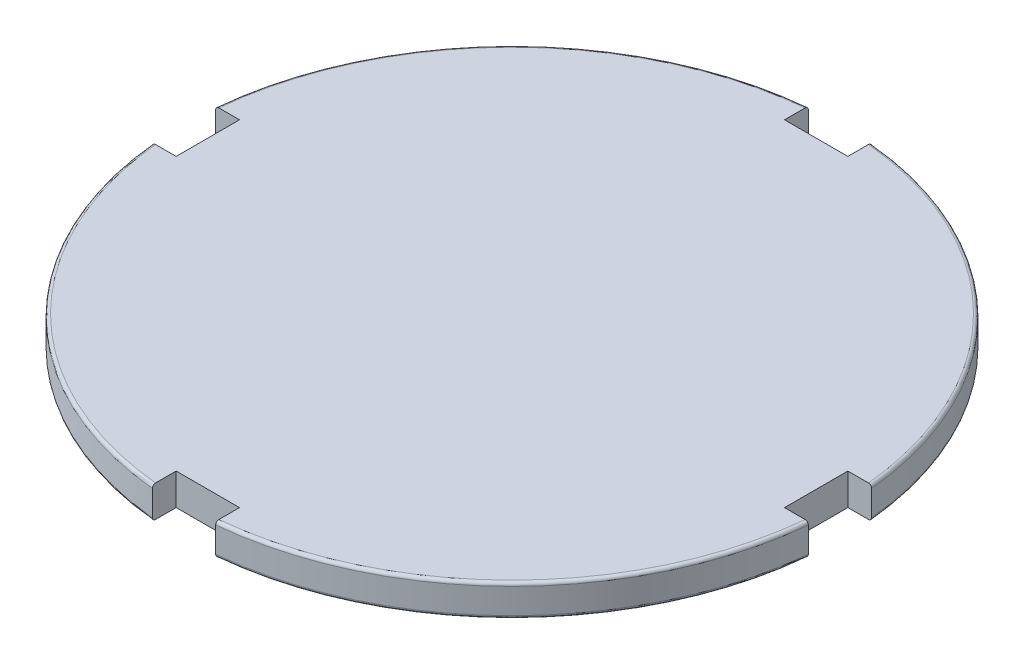
SolidWorks part; units mm, degrees
ref_plane "Front" through (0, 0, 0) normal (0, 0, 1) x (1, 0, 0)
ref_plane "Top" through (0, 0, 0) normal (0, 1, 0) x (1, 0, 0)
ref_plane "Right" through (0, 0, 0) normal (1, 0, 0) x (0, 0, -1)
sketch "Sketch2" plane through (0, 0, 0) normal (0, 1, 0) x (1, 0, 0)
  circle A0 centre (0, 0) radius 66.04
  dimension "D1" = 132.08
extrude "Boss-Extrude1" add sketch "Sketch2" along normal blind 6.35
fillet "Fillet1" radius 0.635 2 edges at (0, 0, 66.04) (0, 6.35, 66.04)
sketch "Sketch4" plane through (0, 0, 0) normal (0, -1, 0) x (1, 0, 0)
  line L0 (0, -75.0224) -> (0, 83.7175) construction
  line L1 (-82.7142, 0) -> (82.2683, 0) construction
  line L2 (74.911, 6.35) -> (74.911, -6.35)
  line L3 (0, -11.0767) -> (60.96, -11.0767) construction
  line L4 (74.911, -6.35) -> (60.96, -6.35)
  line L5 (74.911, 6.35) -> (60.96, 6.35)
  line L6 (60.96, 6.35) -> (60.96, -6.35)
  line L7 (6.35, -60.96) -> (-6.35, -60.96)
  line L8 (-6.35, -74.911) -> (-6.35, -60.96)
  line L9 (6.35, -74.911) -> (-6.35, -74.911)
  line L10 (6.35, -74.911) -> (6.35, -60.96)
  line L11 (-60.96, -6.35) -> (-60.96, 6.35)
  line L12 (-74.911, 6.35) -> (-60.96, 6.35)
  line L13 (-74.911, -6.35) -> (-74.911, 6.35)
  line L14 (-74.911, -6.35) -> (-60.96, -6.35)
  line L15 (-6.35, 60.96) -> (6.35, 60.96)
  line L16 (6.35, 74.911) -> (6.35, 60.96)
  line L17 (-6.35, 74.911) -> (6.35, 74.911)
  line L18 (-6.35, 74.911) -> (-6.35, 60.96)
  point P8 (74.911, 0)
  point P27 (0, 0)
  dimension "D1" = 6.35
  dimension "D2" = 60.96
  dimension "D3" = 4
extrude "Cut-Extrude1" cut sketch "Sketch4" against normal through all
